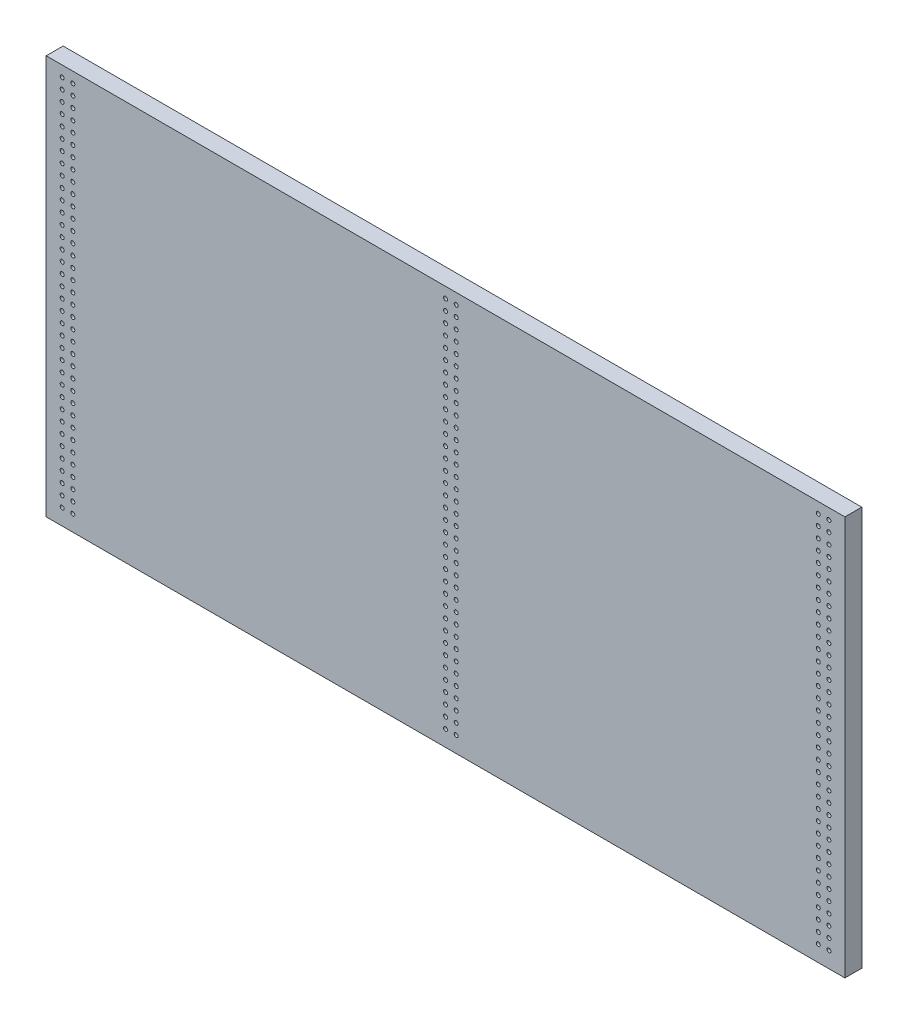
SolidWorks part; units mm, degrees
ref_plane "Front Plane" through (0, 0, 0) normal (0, 0, 1) x (1, 0, 0)
ref_plane "Top Plane" through (0, 0, 0) normal (0, 1, 0) x (1, 0, 0)
ref_plane "Right Plane" through (0, 0, 0) normal (1, 0, 0) x (0, 0, -1)
sketch "Sketch1" plane through (0, 0, 0) normal (0, 0, 1) x (1, 0, 0)
  line L0 (150, 150) -> (150, 0) construction
  line L1 (0, 0) -> (300, 0)
  line L2 (0, 0) -> (0, 150)
  line L3 (0, 150) -> (300, 150)
  line L4 (300, 0) -> (300, 150)
  circle A0 centre (6, 146) radius 0.75
  circle A1 centre (10, 146) radius 0.75
  circle A2 centre (6, 142) radius 0.75
  circle A3 centre (10, 142) radius 0.75
  circle A4 centre (6, 138) radius 0.75
  circle A5 centre (10, 138) radius 0.75
  circle A6 centre (6, 134) radius 0.75
  circle A7 centre (10, 134) radius 0.75
  circle A8 centre (6, 130) radius 0.75
  circle A9 centre (10, 130) radius 0.75
  circle A10 centre (6, 126) radius 0.75
  circle A11 centre (10, 126) radius 0.75
  circle A12 centre (6, 122) radius 0.75
  circle A13 centre (10, 122) radius 0.75
  circle A14 centre (6, 118) radius 0.75
  circle A15 centre (10, 118) radius 0.75
  circle A16 centre (6, 114) radius 0.75
  circle A17 centre (10, 114) radius 0.75
  circle A18 centre (6, 110) radius 0.75
  circle A19 centre (10, 110) radius 0.75
  circle A20 centre (6, 106) radius 0.75
  circle A21 centre (10, 106) radius 0.75
  circle A22 centre (6, 102) radius 0.75
  circle A23 centre (10, 102) radius 0.75
  circle A24 centre (6, 98) radius 0.75
  circle A25 centre (10, 98) radius 0.75
  circle A26 centre (6, 94) radius 0.75
  circle A27 centre (10, 94) radius 0.75
  circle A28 centre (6, 90) radius 0.75
  circle A29 centre (10, 90) radius 0.75
  circle A30 centre (6, 86) radius 0.75
  circle A31 centre (10, 86) radius 0.75
  circle A32 centre (6, 82) radius 0.75
  circle A33 centre (10, 82) radius 0.75
  circle A34 centre (6, 78) radius 0.75
  circle A35 centre (10, 78) radius 0.75
  circle A36 centre (6, 74) radius 0.75
  circle A37 centre (10, 74) radius 0.75
  circle A38 centre (6, 70) radius 0.75
  circle A39 centre (10, 70) radius 0.75
  circle A40 centre (6, 66) radius 0.75
  circle A41 centre (10, 66) radius 0.75
  circle A42 centre (6, 62) radius 0.75
  circle A43 centre (10, 62) radius 0.75
  circle A44 centre (6, 58) radius 0.75
  circle A45 centre (10, 58) radius 0.75
  circle A46 centre (6, 54) radius 0.75
  circle A47 centre (10, 54) radius 0.75
  circle A48 centre (6, 50) radius 0.75
  circle A49 centre (10, 50) radius 0.75
  circle A50 centre (6, 46) radius 0.75
  circle A51 centre (10, 46) radius 0.75
  circle A52 centre (6, 42) radius 0.75
  circle A53 centre (10, 42) radius 0.75
  circle A54 centre (6, 38) radius 0.75
  circle A55 centre (10, 38) radius 0.75
  circle A56 centre (6, 34) radius 0.75
  circle A57 centre (10, 34) radius 0.75
  circle A58 centre (6, 30) radius 0.75
  circle A59 centre (10, 30) radius 0.75
  circle A60 centre (6, 26) radius 0.75
  circle A61 centre (10, 26) radius 0.75
  circle A62 centre (6, 22) radius 0.75
  circle A63 centre (10, 22) radius 0.75
  circle A64 centre (6, 18) radius 0.75
  circle A65 centre (10, 18) radius 0.75
  circle A66 centre (6, 14) radius 0.75
  circle A67 centre (10, 14) radius 0.75
  circle A68 centre (6, 10) radius 0.75
  circle A69 centre (10, 10) radius 0.75
  circle A70 centre (6, 6) radius 0.75
  circle A71 centre (10, 6) radius 0.75
  circle A72 centre (290, 6) radius 0.75
  circle A73 centre (294, 6) radius 0.75
  circle A74 centre (290, 10) radius 0.75
  circle A75 centre (294, 10) radius 0.75
  circle A76 centre (290, 14) radius 0.75
  circle A77 centre (294, 14) radius 0.75
  circle A78 centre (290, 18) radius 0.75
  circle A79 centre (294, 18) radius 0.75
  circle A80 centre (290, 22) radius 0.75
  circle A81 centre (294, 22) radius 0.75
  circle A82 centre (290, 26) radius 0.75
  circle A83 centre (294, 26) radius 0.75
  circle A84 centre (290, 30) radius 0.75
  circle A85 centre (294, 30) radius 0.75
  circle A86 centre (290, 34) radius 0.75
  circle A87 centre (294, 34) radius 0.75
  circle A88 centre (290, 38) radius 0.75
  circle A89 centre (294, 38) radius 0.75
  circle A90 centre (290, 42) radius 0.75
  circle A91 centre (294, 42) radius 0.75
  circle A92 centre (150, 146) radius 0.75
  circle A93 centre (154, 146) radius 0.75
  circle A94 centre (150, 142) radius 0.75
  circle A95 centre (154, 142) radius 0.75
  circle A96 centre (150, 138) radius 0.75
  circle A97 centre (154, 138) radius 0.75
  circle A98 centre (150, 134) radius 0.75
  circle A99 centre (154, 134) radius 0.75
  circle A100 centre (150, 130) radius 0.75
  circle A101 centre (154, 130) radius 0.75
  circle A102 centre (150, 126) radius 0.75
  circle A103 centre (154, 126) radius 0.75
  circle A104 centre (150, 122) radius 0.75
  circle A105 centre (154, 122) radius 0.75
  circle A106 centre (150, 118) radius 0.75
  circle A107 centre (154, 118) radius 0.75
  circle A108 centre (150, 114) radius 0.75
  circle A109 centre (154, 114) radius 0.75
  circle A110 centre (150, 110) radius 0.75
  circle A111 centre (154, 110) radius 0.75
  circle A112 centre (150, 106) radius 0.75
  circle A113 centre (154, 106) radius 0.75
  circle A114 centre (150, 102) radius 0.75
  circle A115 centre (154, 102) radius 0.75
  circle A116 centre (150, 98) radius 0.75
  circle A117 centre (154, 98) radius 0.75
  circle A118 centre (150, 94) radius 0.75
  circle A119 centre (154, 94) radius 0.75
  circle A120 centre (150, 90) radius 0.75
  circle A121 centre (154, 90) radius 0.75
  circle A122 centre (150, 86) radius 0.75
  circle A123 centre (154, 86) radius 0.75
  circle A124 centre (150, 82) radius 0.75
  circle A125 centre (154, 82) radius 0.75
  circle A126 centre (150, 78) radius 0.75
  circle A127 centre (154, 78) radius 0.75
  circle A128 centre (150, 74) radius 0.75
  circle A129 centre (154, 74) radius 0.75
  circle A130 centre (150, 70) radius 0.75
  circle A131 centre (154, 70) radius 0.75
  circle A132 centre (150, 66) radius 0.75
  circle A133 centre (154, 66) radius 0.75
  circle A134 centre (150, 62) radius 0.75
  circle A135 centre (154, 62) radius 0.75
  circle A136 centre (150, 58) radius 0.75
  circle A137 centre (154, 58) radius 0.75
  circle A138 centre (150, 54) radius 0.75
  circle A139 centre (154, 54) radius 0.75
  circle A140 centre (150, 50) radius 0.75
  circle A141 centre (154, 50) radius 0.75
  circle A142 centre (150, 46) radius 0.75
  circle A143 centre (154, 46) radius 0.75
  circle A144 centre (150, 42) radius 0.75
  circle A145 centre (154, 42) radius 0.75
  circle A146 centre (150, 38) radius 0.75
  circle A147 centre (154, 38) radius 0.75
  circle A148 centre (150, 34) radius 0.75
  circle A149 centre (154, 34) radius 0.75
  circle A150 centre (290, 46) radius 0.75
  circle A151 centre (294, 46) radius 0.75
  circle A152 centre (290, 50) radius 0.75
  circle A153 centre (294, 50) radius 0.75
  circle A154 centre (290, 54) radius 0.75
  circle A155 centre (294, 54) radius 0.75
  circle A156 centre (290, 58) radius 0.75
  circle A157 centre (294, 58) radius 0.75
  circle A158 centre (290, 62) radius 0.75
  circle A159 centre (294, 62) radius 0.75
  circle A160 centre (290, 66) radius 0.75
  circle A161 centre (294, 66) radius 0.75
  circle A162 centre (290, 70) radius 0.75
  circle A163 centre (294, 70) radius 0.75
  circle A164 centre (290, 74) radius 0.75
  circle A165 centre (294, 74) radius 0.75
  circle A166 centre (290, 78) radius 0.75
  circle A167 centre (294, 78) radius 0.75
  circle A168 centre (290, 82) radius 0.75
  circle A169 centre (294, 82) radius 0.75
  circle A170 centre (290, 86) radius 0.75
  circle A171 centre (294, 86) radius 0.75
  circle A172 centre (290, 90) radius 0.75
  circle A173 centre (294, 90) radius 0.75
  circle A174 centre (290, 94) radius 0.75
  circle A175 centre (294, 94) radius 0.75
  circle A176 centre (290, 98) radius 0.75
  circle A177 centre (294, 98) radius 0.75
  circle A178 centre (290, 102) radius 0.75
  circle A179 centre (294, 102) radius 0.75
  circle A180 centre (290, 106) radius 0.75
  circle A181 centre (294, 106) radius 0.75
  circle A182 centre (290, 110) radius 0.75
  circle A183 centre (294, 110) radius 0.75
  circle A184 centre (290, 114) radius 0.75
  circle A185 centre (294, 114) radius 0.75
  circle A186 centre (290, 118) radius 0.75
  circle A187 centre (294, 118) radius 0.75
  circle A188 centre (290, 122) radius 0.75
  circle A189 centre (294, 122) radius 0.75
  circle A190 centre (290, 126) radius 0.75
  circle A191 centre (294, 126) radius 0.75
  circle A192 centre (290, 130) radius 0.75
  circle A193 centre (294, 130) radius 0.75
  circle A194 centre (290, 134) radius 0.75
  circle A195 centre (294, 134) radius 0.75
  circle A196 centre (290, 138) radius 0.75
  circle A197 centre (294, 138) radius 0.75
  circle A198 centre (290, 142) radius 0.75
  circle A199 centre (294, 142) radius 0.75
  circle A200 centre (290, 146) radius 0.75
  circle A201 centre (294, 146) radius 0.75
  circle A202 centre (150, 30) radius 0.75
  circle A203 centre (154, 30) radius 0.75
  circle A204 centre (150, 26) radius 0.75
  circle A205 centre (154, 26) radius 0.75
  circle A206 centre (150, 22) radius 0.75
  circle A207 centre (154, 22) radius 0.75
  circle A208 centre (150, 18) radius 0.75
  circle A209 centre (154, 18) radius 0.75
  circle A210 centre (150, 14) radius 0.75
  circle A211 centre (154, 14) radius 0.75
  circle A212 centre (150, 10) radius 0.75
  circle A213 centre (154, 10) radius 0.75
  circle A214 centre (150, 6) radius 0.75
  circle A215 centre (154, 6) radius 0.75
  dimension "D3" = 1.5
  dimension "D4" = 1.5
  dimension "D5" = 36
  dimension "D6" = 4
  dimension "D1" = 300
  dimension "D2" = 150
  dimension "D7" = 4
  dimension "D8" = 2
  dimension "D10" = 4
  dimension "D11" = 6
  dimension "D12" = 6
  dimension "D9" = 150
extrude "Boss-Extrude1" add sketch "Sketch1" along normal blind 6.35
